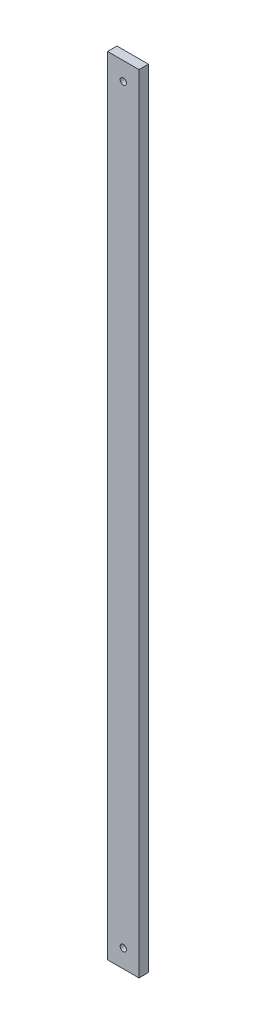
SolidWorks part; units mm, degrees
ref_plane "Front Plane" through (0, 0, 0) normal (0, 0, 1) x (1, 0, 0)
ref_plane "Top Plane" through (0, 0, 0) normal (0, 1, 0) x (1, 0, 0)
ref_plane "Right Plane" through (0, 0, 0) normal (1, 0, 0) x (0, 0, -1)
sketch "Sketch1" plane through (0, 0, 0) normal (0, 1, 0) x (1, 0, 0)
  line L1 (0, 0) -> (20, 0)
  line L2 (0, 0) -> (0, 6)
  line L3 (0, 6) -> (20, 6)
  line L4 (20, 0) -> (20, 6)
  dimension "D1" = 6
  dimension "D2" = 20
extrude "Boss-Extrude1" add sketch "Sketch1" along normal blind 500
sketch "Sketch2" plane through (0, 0, -6) normal (0, 0, -1) x (-1, 0, 0)
  line L0 (-20, 500) -> (0, 500) construction
  line L1 (0, 500) -> (0, 0) construction
  line L2 (-20, 500) -> (-20, 0) construction
  line L3 (-20, 0) -> (0, 0) construction
  circle A0 centre (-10, 488.5) radius 2
  circle A1 centre (-10, 11.5) radius 2
  dimension "D1" = 11.5
  dimension "D3" = 10
  dimension "D2" = 10
  dimension "D4" = 11.5
extrude "Cut-Extrude1" cut sketch "Sketch2" against normal blind 10
